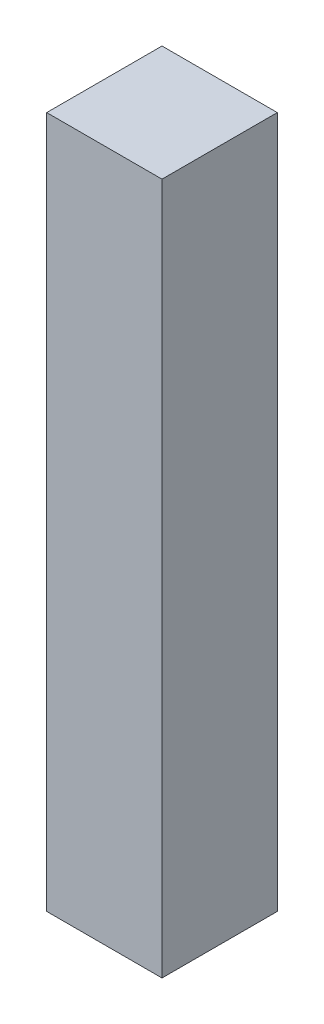
SolidWorks part; units mm, degrees
material "Mahogany"
ref_plane "Front Plane" through (0, 0, 0) normal (0, 0, 1) x (1, 0, 0)
ref_plane "Top Plane" through (0, 0, 0) normal (0, 1, 0) x (1, 0, 0)
ref_plane "Right Plane" through (0, 0, 0) normal (1, 0, 0) x (0, 0, -1)
sketch "Sketch1" plane through (0, 0, 0) normal (0, 1, 0) x (1, 0, 0)
  line L1 (-2.5, 2.5) -> (2.5, 2.5)
  line L2 (-2.5, 2.5) -> (-2.5, -2.5)
  line L3 (-2.5, -2.5) -> (2.5, -2.5)
  line L4 (2.5, 2.5) -> (2.5, -2.5)
  line L5 (-2.5, 2.5) -> (2.5, -2.5) construction
  line L6 (-2.5, -2.5) -> (2.5, 2.5) construction
  point P0 (0, 0)
  dimension "D1" = 5
  dimension "D2" = 5
extrude "Boss-Extrude1" add sketch "Sketch1" along normal blind 30
